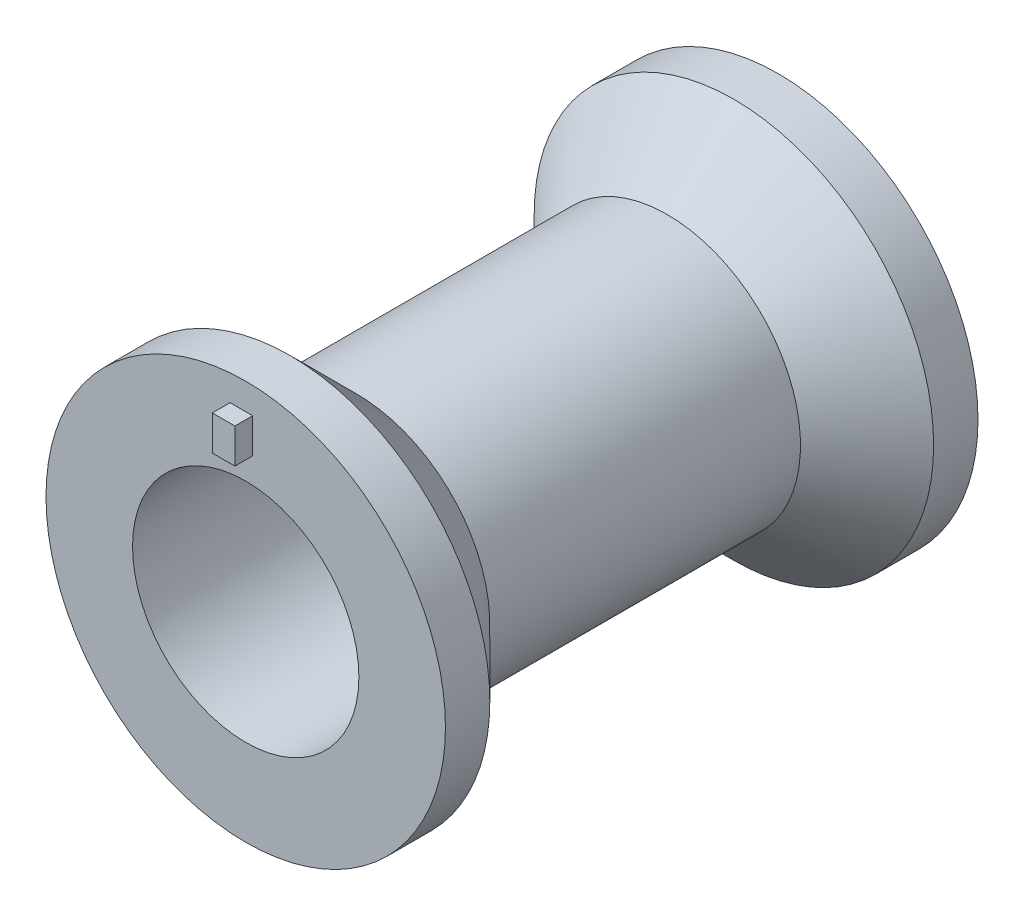
SolidWorks part; units mm, degrees
ref_plane "Front Plane" through (0, 0, 0) normal (0, 0, 1) x (1, 0, 0)
ref_plane "Top Plane" through (0, 0, 0) normal (0, 1, 0) x (1, 0, 0)
ref_plane "Right Plane" through (0, 0, 0) normal (1, 0, 0) x (0, 0, -1)
sketch "Sketch2" plane through (0, 0, 0) normal (0, 0, 1) x (1, 0, 0)
  circle A0 centre (0, 0) radius 22.5
  circle A1 centre (0, 0) radius 12.75
  dimension "D1" = 45
  dimension "D2" = 25.5
extrude "Boss-Extrude1" add sketch "Sketch2" along normal blind 60
sketch "Sketch3" plane through (0, 0, 0) normal (0, 1, 0) x (1, 0, 0)
  line L0 (0, 0) -> (22.5, 0) construction
  line L1 (22.5, 0) -> (-22.5, 0) construction
  line L2 (22.5, -60) -> (22.5, 0) construction
  line L3 (22.5, 0) -> (22.5, -5) construction
  line L4 (22.5, -5) -> (15, -5) construction
  line L6 (22.5, -5) -> (22.5, -55)
  line L7 (22.5, -5) -> (15, -12.5)
  line L8 (15, -12.5) -> (15, -47.5)
  line L9 (22.5, -55) -> (15, -55) construction
  line L12 (15, -47.5) -> (22.5, -55)
  dimension "D1" = 50
  dimension "D2" = 35
  dimension "D3" = 7.5
  dimension "D4" = 10.6066
  dimension "D5" = 5
ref_axis "Axis1" through (0, 0, -10.7965) along (0, 0, 1)
revolve "Cut-Revolve1" cut sketch "Sketch3" angle 360 about axis through (0, 0, -10.7965) along (0, 0, 1)
sketch "Sketch4" plane through (0, 0, 60) normal (0, 0, 1) x (1, 0, 0)
  line L0 (-1.7623, 19.5154) -> (-1.7623, 15.5992)
  line L1 (-1.7623, 19.5154) -> (0.7832, 19.5154)
  line L2 (-1.7623, 15.5992) -> (0.7832, 15.5992)
  line L3 (0.7832, 19.5154) -> (0.7832, 15.5992)
extrude "Boss-Extrude2" add sketch "Sketch4" along normal blind 2
